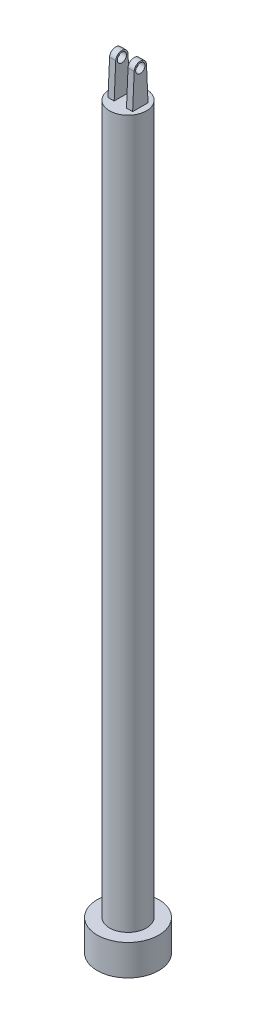
SolidWorks part; units mm, degrees
ref_plane "Front Plane" through (0, 0, 0) normal (0, 0, 1) x (1, 0, 0)
ref_plane "Top Plane" through (0, 0, 0) normal (0, 1, 0) x (1, 0, 0)
ref_plane "Right Plane" through (0, 0, 0) normal (1, 0, 0) x (0, 0, -1)
sketch "Sketch1" plane through (0, 0, 0) normal (0, 0, 1) x (1, 0, 0)
  line L0 (0, 0) -> (0, 110) construction
  line L1 (0, 0) -> (5, 0)
  line L2 (5, 0) -> (5, 5)
  line L3 (5, 5) -> (3, 5)
  line L4 (3, 5) -> (3, 110)
  line L5 (3, 110) -> (0, 110)
  line L6 (0, 110) -> (0, 0)
  line L8 (0, 110) -> (3, 110)
  line L9 (0, 110) -> (0, 120)
  line L10 (0, 120) -> (3, 120)
  line L11 (3, 110) -> (3, 120)
  dimension "D1" = 110
  dimension "D2" = 5
  dimension "D3" = 3
  dimension "D4" = 5
  dimension "D5" = 10
revolve "Revolve1" add sketch "Sketch1" angle 360 about L0
sketch "Sketch2" plane through (0, 120, 0) normal (0, 1, 0) x (1, 0, 0)
  line L0 (-1, 1.25) -> (-1, -1.25)
  line L1 (-2, 1.25) -> (2, 1.25)
  line L2 (-2, 1.25) -> (-2, -1.25)
  line L3 (-2, -1.25) -> (2, -1.25)
  line L4 (2, 1.25) -> (2, -1.25)
  line L5 (-2, 1.25) -> (2, -1.25) construction
  line L6 (-2, -1.25) -> (2, 1.25) construction
  line L7 (1, 1.25) -> (1, -1.25)
  point P0 (0, 0)
  dimension "D1" = 1
  dimension "D2" = 1
  dimension "D3" = 4
  dimension "D4" = 2.5
extrude "Boss-Extrude2" add sketch "Sketch2" along normal blind 7 contours L2 L3 L0 L1 | L1 L7 L3 L4
sketch "Sketch3" plane through (-2, 0, 0) normal (-1, 0, 0) x (0, 0, 1)
  line L0 (0, 125.5) -> (0, 120) construction
  line L1 (1.25, 120) -> (0.999, 125.5452)
  line L2 (-1.25, 120) -> (1.25, 120) construction
  line L3 (-1.25, 120) -> (-0.999, 125.5452)
  line L8 (-1.25, 120) -> (1.25, 120)
  line L9 (1.25, 120) -> (1.25, 127)
  line L10 (1.25, 127) -> (-1.25, 127)
  line L11 (-1.25, 127) -> (-1.25, 120)
  line L13 (1.25, 120) -> (1.25, 127)
  line L14 (1.25, 127) -> (-1.25, 127)
  line L15 (-1.25, 127) -> (-1.25, 120)
  circle A0 centre (0, 125.5) radius 0.75
  arc A1 (0.999, 125.5452) -> (-0.999, 125.5452) centre (0, 125.5) ccw
  dimension "D1" = 1.5
  dimension "D2" = 2
  dimension "D3" = 5.5
  dimension "D4" = 0
extrude "Cut-Extrude1" cut sketch "Sketch3" against normal blind 7
ref_plane "Plane1" through (1, 120, -1.25) normal (0, 0, 1) x (1, 0, 0)
